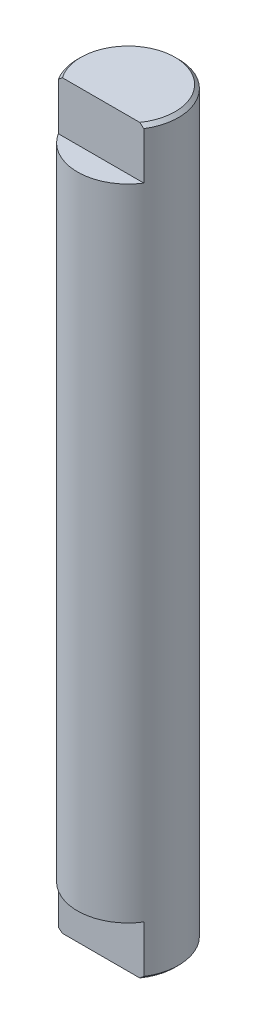
SolidWorks part; units mm, degrees
ref_plane "Plan de face" through (0, 0, 0) normal (0, 0, 1) x (1, 0, 0)
ref_plane "Plan de dessus" through (0, 0, 0) normal (0, 1, 0) x (1, 0, 0)
ref_plane "Plan de droite" through (0, 0, 0) normal (1, 0, 0) x (0, 0, -1)
ref_plane "Plan1" through (0, 0, 10.4) normal (0, 0, 1) x (1, 0, 0)
sketch "Esquisse1" plane through (0, 0, 10.4) normal (0, 0, 1) x (1, 0, 0)
  line L0 (23.2578, 8.6873) -> (21.7578, 8.6873)
  line L1 (21.7578, 8.6873) -> (21.7578, -13.3127)
  line L2 (21.7578, -13.3127) -> (23.2578, -13.3127)
  line L3 (23.2578, -13.3127) -> (23.2578, 8.6873)
  line L4 (21.7578, 8.6873) -> (21.7578, -13.3127) construction
  dimension "D1" = 22
revolve "Révolution1" add sketch "Esquisse1" angle 360 about L4
sketch "Esquisse2" plane through (0, 8.6873, 0) normal (0, 1, 0) x (-1, 0, 0)
  line L0 (-23.0267, 11.2) -> (-20.489, 11.2)
  arc A0 (-20.489, 11.2) -> (-23.0267, 11.2) centre (-21.7578, 10.4) ccw
extrude "Enlèv. mat.-Extru.1" cut sketch "Esquisse2" against normal blind 1.5
sketch "Esquisse3" plane through (0, -13.3127, 0) normal (0, -1, 0) x (1, 0, 0)
  line L0 (20.489, 11.2) -> (23.0267, 11.2)
  arc A0 (23.0267, 11.2) -> (20.489, 11.2) centre (21.7578, 10.4) ccw
extrude "Enlèv. mat.-Extru.2" cut sketch "Esquisse3" against normal blind 1.5
chamfer "Chanfrein1" distance 0.1 angle 45 1 edges at (21.7578, 8.6873, 8.9)
chamfer "Chanfrein2" distance 0.1 angle 45 1 edges at (21.7578, -13.3127, 8.9)
